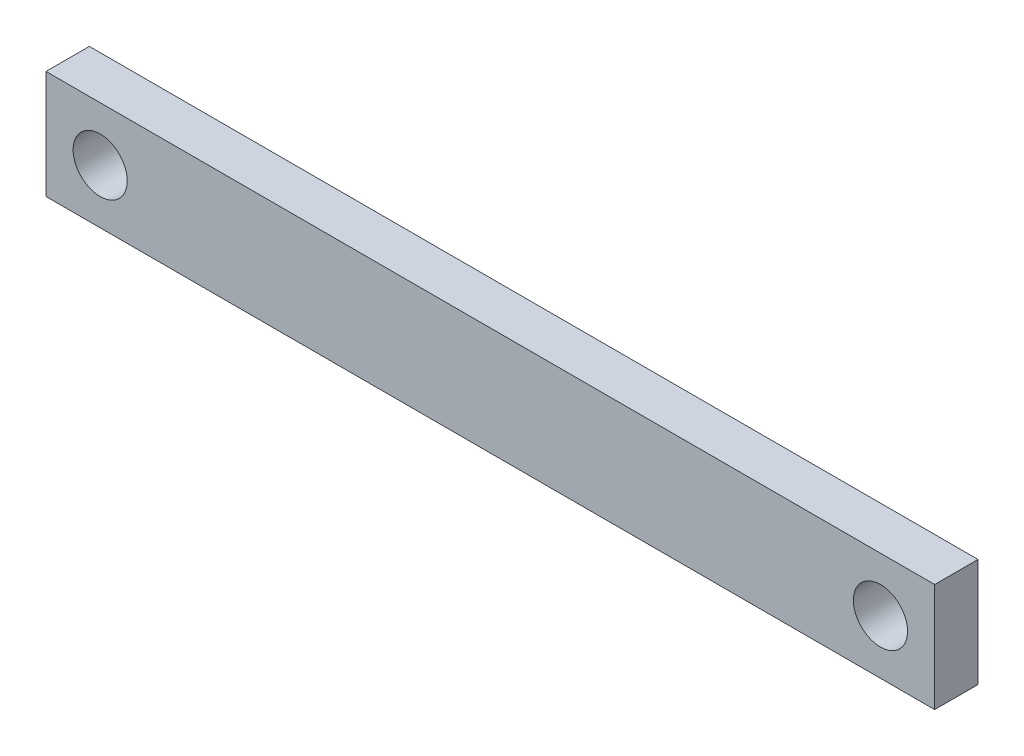
SolidWorks part; units mm, degrees
material "自訂玻璃纖維"
ref_plane "前基準面" through (0, 0, 0) normal (0, 0, 1) x (1, 0, 0)
ref_plane "上基準面" through (0, 0, 0) normal (0, 1, 0) x (1, 0, 0)
ref_plane "右基準面" through (0, 0, 0) normal (1, 0, 0) x (0, 0, -1)
sketch "草圖1" plane through (0, 0, 0) normal (0, 0, 1) x (1, 0, 0)
  line L1 (-17.2084, 11.8202) -> (23.7916, 11.8202)
  line L2 (-17.2084, 11.8202) -> (-17.2084, 6.8202)
  line L3 (-17.2084, 6.8202) -> (23.7916, 6.8202)
  line L4 (23.7916, 11.8202) -> (23.7916, 6.8202)
  circle A0 centre (-14.7084, 9.3202) radius 1.25
  circle A1 centre (21.2916, 9.3202) radius 1.25
  dimension "D3" = 2.5
  dimension "D4" = 2.5
  dimension "D5" = 2.5
  dimension "D6" = 2.5
  dimension "D7" = 2.5
  dimension "D8" = 2.5
  dimension "D1" = 41
  dimension "D2" = 5
extrude "填料-伸長1" add sketch "草圖1" along normal blind 2
